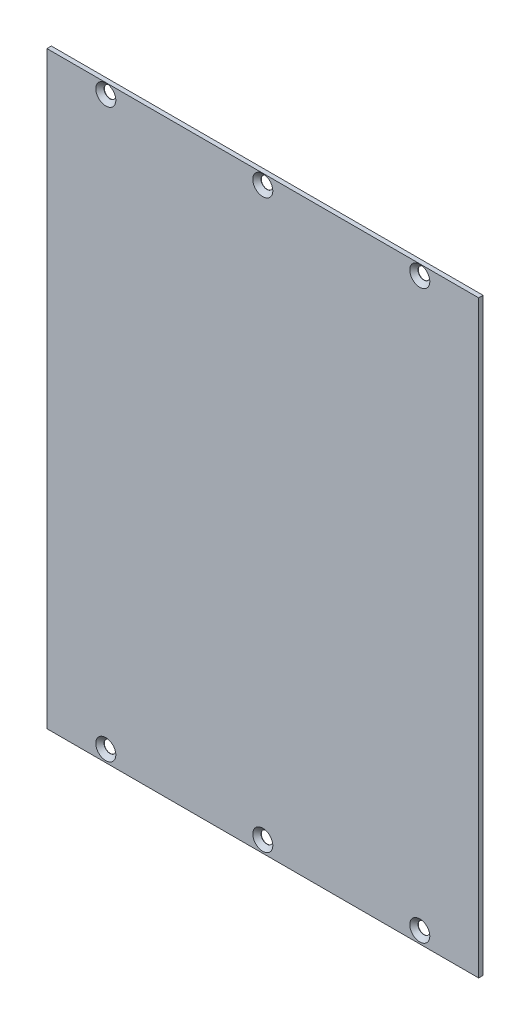
SolidWorks part; units mm, degrees
ref_plane "Спереди" through (0, 0, 0) normal (0, 0, 1) x (1, 0, 0)
ref_plane "Сверху" through (0, 0, 0) normal (0, 1, 0) x (1, 0, 0)
ref_plane "Справа" through (0, 0, 0) normal (1, 0, 0) x (0, 0, -1)
sketch "Эскиз1" plane through (0, 0, 0) normal (0, 0, 1) x (1, 0, 0)
  line L1 (0, 0) -> (146.6, 0)
  line L2 (0, 0) -> (0, 200)
  line L3 (0, 200) -> (146.6, 200)
  line L4 (146.6, 0) -> (146.6, 200)
  dimension "D1" = 146.6
  dimension "D2" = 200
extrude "Бобышка-Вытянуть1" add sketch "Эскиз1" along normal blind 1.5
sketch "Эскиз2" plane through (0, 0, 1.5) normal (0, 0, 1) x (1, 0, 0)
  line L0 (0, 0) -> (146.6, 0) construction
  line L1 (0, 200) -> (0, 0) construction
  line L2 (146.6, 200) -> (0, 200) construction
  circle A0 centre (20, 4) radius 2
  circle A1 centre (20, 196.5) radius 2
  circle A2 centre (73.3, 196.5) radius 2
  circle A3 centre (73.3, 4) radius 2
  circle A4 centre (126.6, 196.5) radius 2
  circle A5 centre (126.6, 4) radius 2
  dimension "D1" = 4
  dimension "D2" = 4
  dimension "D3" = 20
  dimension "D4" = 3.5
  dimension "D5" = 3
extrude "Вырез-Вытянуть1" cut sketch "Эскиз2" against normal through all
chamfer "Фаска1" distance 1.4 angle 45 6 edges at (128.6, 196.5, 1.5) (75.3, 196.5, 1.5) (22, 196.5, 1.5) (128.6, 4, 1.5) (75.3, 4, 1.5) (22, 4, 1.5)
